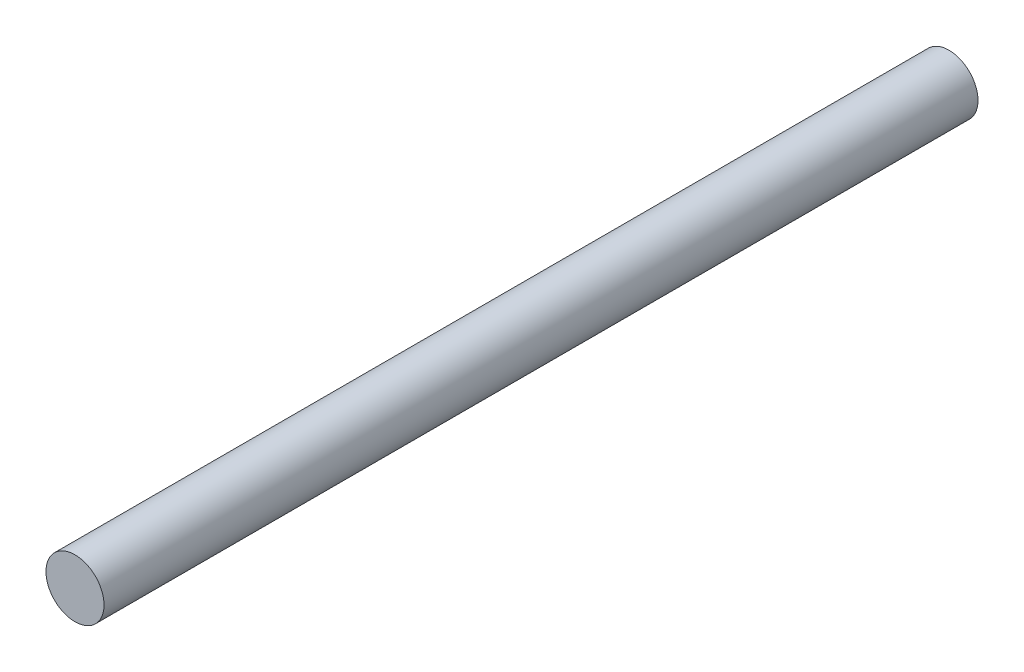
SolidWorks part; units mm, degrees
ref_plane "Front Plane" through (0, 0, 0) normal (0, 0, 1) x (1, 0, 0)
ref_plane "Top Plane" through (0, 0, 0) normal (0, 1, 0) x (1, 0, 0)
ref_plane "Right Plane" through (0, 0, 0) normal (1, 0, 0) x (0, 0, -1)
sketch "Sketch1" plane through (0, 0, 0) normal (0, 0, 1) x (1, 0, 0)
  circle A0 centre (0, 0) radius 4
  dimension "D1" = 8
extrude "Boss-Extrude1" add sketch "Sketch1" along normal blind 120.4
